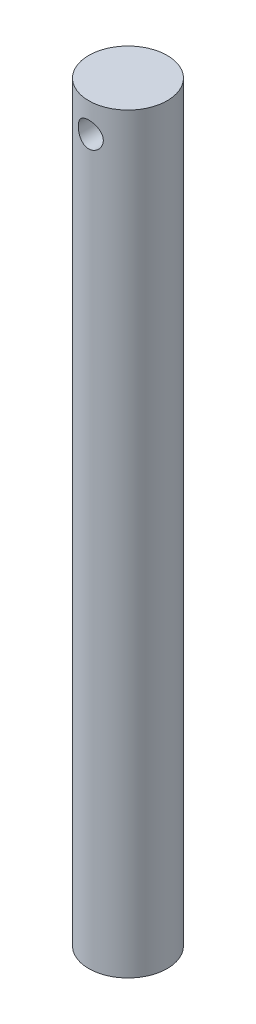
SolidWorks part; units mm, degrees
ref_plane "Front Plane" through (0, 0, 0) normal (0, 0, 1) x (1, 0, 0)
ref_plane "Top Plane" through (0, 0, 0) normal (0, 1, 0) x (1, 0, 0)
ref_plane "Right Plane" through (0, 0, 0) normal (1, 0, 0) x (0, 0, -1)
sketch "Sketch1" plane through (0, 0, 0) normal (0, 1, 0) x (1, 0, 0)
  circle A0 centre (0, 0) radius 9.4
  dimension "D1" = 18.8
extrude "Boss-Extrude1" add sketch "Sketch1" along normal blind 180
sketch "Sketch2" plane through (0, 0, 0) normal (0, 0, 1) x (1, 0, 0)
  line L0 (9.4, 180) -> (-9.4, 180) construction
  circle A0 centre (0, 173) radius 3
  dimension "D1" = 6
  dimension "D2" = 7
extrude "Cut-Extrude1" cut sketch "Sketch2" against normal through all both and the other way through all
